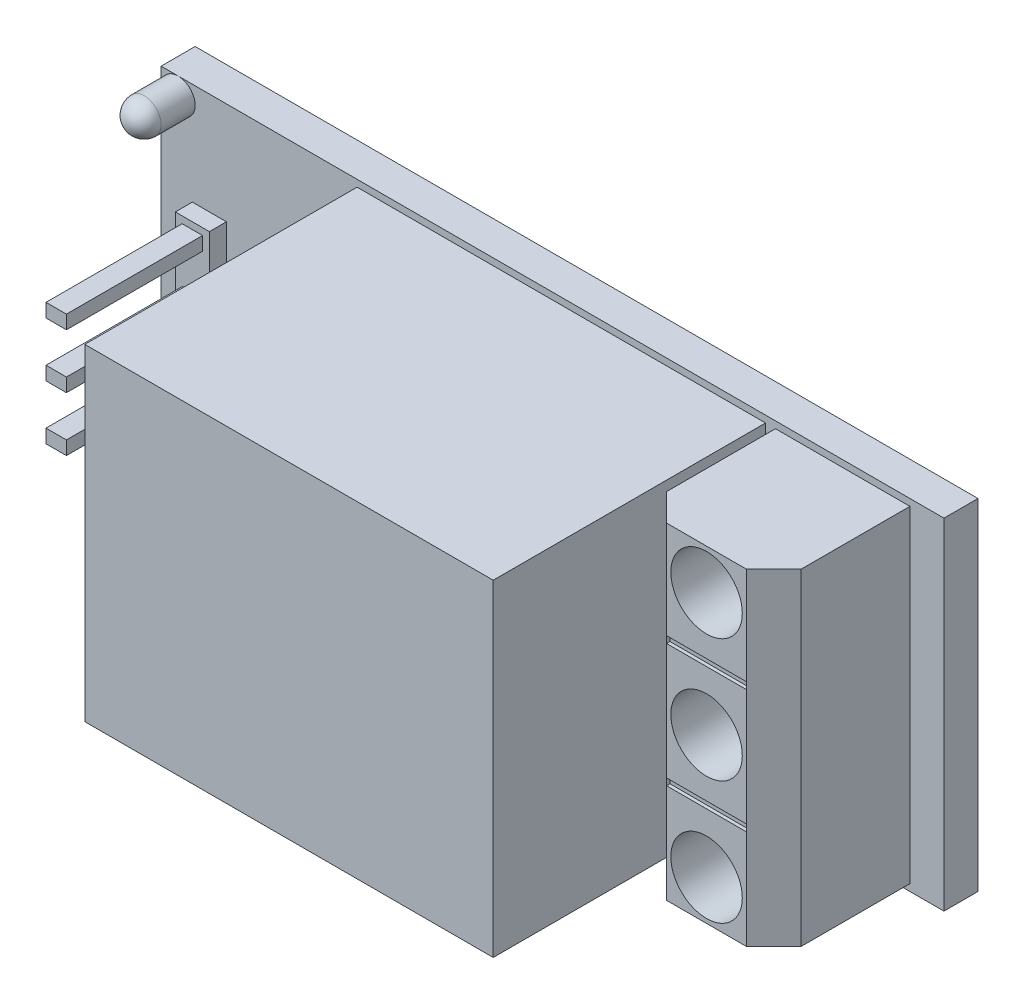
SolidWorks part; units mm, degrees
ref_plane "Front Plane" through (0, 0, 0) normal (0, 0, 1) x (1, 0, 0)
ref_plane "Top Plane" through (0, 0, 0) normal (0, 1, 0) x (1, 0, 0)
ref_plane "Right Plane" through (0, 0, 0) normal (1, 0, 0) x (0, 0, -1)
sketch "Sketch1" plane through (0, 0, 0) normal (0, 0, 1) x (1, 0, 0)
  line L1 (0, 0) -> (23, 0)
  line L2 (0, 0) -> (0, -10)
  line L3 (0, -10) -> (23, -10)
  line L4 (23, 0) -> (23, -10)
  dimension "D1" = 10
  dimension "D2" = 23
extrude "Boss-Extrude1" add sketch "Sketch1" along normal blind 1
sketch "Sketch2" plane through (0, 0, 1) normal (0, 0, 1) x (1, 0, 0)
  line L0 (23, 0) -> (0, 0) construction
  line L1 (22, -0.2) -> (18.05, -0.2)
  line L2 (22, -0.2) -> (22, -9.8)
  line L3 (22, -9.8) -> (18.05, -9.8)
  line L4 (18.05, -0.2) -> (18.05, -9.8)
  dimension "D1" = 1
  dimension "D2" = 0.2
  dimension "D3" = 0.2
  dimension "D4" = 3.95
extrude "Boss-Extrude2" add sketch "Sketch2" along normal blind 4
sketch "Sketch5" plane through (0, 0, 1) normal (0, 0, 1) x (1, 0, 0)
  line L1 (17.7578, -0.2) -> (5.7578, -0.2)
  line L2 (17.7578, -0.2) -> (17.7578, -9.8)
  line L3 (17.7578, -9.8) -> (5.7578, -9.8)
  line L4 (5.7578, -0.2) -> (5.7578, -9.8)
  point P4 (0, 0)
  point P5 (16.7151, -0.2)
  dimension "D1" = 12
extrude "Boss-Extrude3" add sketch "Sketch5" along normal blind 8
sketch "Sketch6" plane through (0, -9.8, 0) normal (0, -1, 0) x (1, 0, 0)
  line L0 (21.2, 5) -> (22, 4.2)
  line L1 (18.05, 5) -> (22, 5) construction
  line L2 (22, 5) -> (22, 1) construction
  line L3 (22, 4.2) -> (22, 5)
  line L4 (22, 5) -> (21.2, 5)
  line L5 (18.05, 5) -> (18.85, 5)
  line L6 (18.85, 5) -> (18.05, 4.2)
  line L7 (18.05, 5) -> (18.05, 1) construction
  line L8 (18.05, 4.2) -> (18.05, 5)
  dimension "D1" = 0.8
  dimension "D2" = 0.8
  dimension "D3" = 1.1314
  dimension "D4" = 0.8
  dimension "D5" = 0.8
  dimension "D6" = 1.1314
extrude "Cut-Extrude1" cut sketch "Sketch6" against normal up to next
sketch "Sketch7" plane through (0, 0, 5) normal (0, 0, 1) x (1, 0, 0)
  line L0 (18.85, -9.8) -> (21.2, -9.8) construction
  line L1 (20.025, -9.8) -> (20.025, -0.2) construction
  line L2 (21.2, -0.2) -> (18.85, -0.2) construction
  line L3 (18.85, -0.2) -> (18.85, -9.8) construction
  line L4 (18.85, -9.8) -> (21.2, -9.8)
  line L5 (18.85, -9.8) -> (18.85, -7.45)
  line L6 (18.85, -7.45) -> (21.2, -7.45)
  line L8 (21.2, -0.2) -> (21.2, -9.8) construction
  line L17 (21.2, -9.8) -> (21.2, -7.45)
  line L18 (21.2, -6.18) -> (21.2, -3.83)
  line L19 (18.85, -3.83) -> (21.2, -3.83)
  line L20 (18.85, -6.18) -> (18.85, -3.83)
  line L21 (18.85, -6.18) -> (21.2, -6.18)
  line L22 (21.2, -2.56) -> (21.2, -0.21)
  line L23 (18.85, -0.21) -> (21.2, -0.21)
  line L24 (18.85, -2.56) -> (18.85, -0.21)
  line L25 (18.85, -2.56) -> (21.2, -2.56)
  circle A0 centre (20.025, -8.625) radius 1.05
  circle A1 centre (20.025, -5.005) radius 1.05
  circle A2 centre (20.025, -1.385) radius 1.05
  point P2 (20.025, -9.8)
  point P10 (18.85, -8.625)
  point P16 (20.025, -8.625)
  dimension "D1" = 2.35
  dimension "D2" = 2.35
  dimension "D4" = 2.1
  dimension "D3" = 3
  dimension "D5" = 3
extrude "Cut-Extrude3" cut sketch "Sketch7" against normal blind 1.5 contours A0 | A1 | A2
sketch "Sketch9" plane through (0, 0, 5) normal (0, 0, 1) x (1, 0, 0)
  line L0 (18.85, -9.8) -> (21.2, -9.8)
  line L1 (18.85, -0.2) -> (18.85, -9.8) construction
  line L2 (18.85, -6.8837) -> (21.2, -6.8837)
  line L3 (18.85, -6.8837) -> (18.85, -6.6837)
  line L4 (18.85, -6.6837) -> (21.2, -6.6837)
  line L5 (21.2, -6.8837) -> (21.2, -6.6837)
  line L6 (21.2, -0.2) -> (21.2, -9.8) construction
  line L8 (18.85, -3.264) -> (21.2, -3.264)
  line L9 (18.85, -3.264) -> (18.85, -3.064)
  line L10 (18.85, -3.064) -> (21.2, -3.064)
  line L11 (21.2, -3.264) -> (21.2, -3.064)
  line M13 (21.2, -9.8) -> (21.2, -0.2)
  line M15 (18.85, -0.2) -> (18.85, -9.8)
  dimension "D1" = 9.6
  dimension "D2" = 0.2
  dimension "D3" = 0.2
extrude "Cut-Extrude4" cut sketch "Sketch9" against normal blind 0.1 contours L4 L2 M15 M13 | L9 L8 L11 L10
sketch "Sketch10" plane through (0, 0, 1) normal (0, 0, 1) x (1, 0, 0)
  line L0 (1.5794, -4.9531) -> (1.5794, -5.1637)
  line L1 (1.9183, -7) -> (0.9183, -7)
  line L2 (1.9183, -7) -> (1.9183, -3)
  line L3 (1.9183, -3) -> (0.9183, -3)
  line L4 (0.9183, -7) -> (0.9183, -3)
  line L5 (23, 0) -> (0, 0) construction
  line L6 (1.5794, -4.9531) -> (1.2044, -4.9531)
  line L7 (1.5794, -3.2531) -> (1.2044, -3.2531)
  line L8 (1.5794, -3.2531) -> (1.5794, -3.4637)
  line L9 (1.5794, -3.4637) -> (1.2044, -3.4637)
  line L10 (1.2044, -3.2531) -> (1.2044, -3.4637)
  line L11 (1.2044, -4.9531) -> (1.2044, -5.1637)
  line L12 (1.5794, -5.1637) -> (1.2044, -5.1637)
  line L13 (1.5794, -6.6531) -> (1.5794, -6.8637)
  line L14 (1.5794, -6.6531) -> (1.2044, -6.6531)
  line L15 (1.2044, -6.6531) -> (1.2044, -6.8637)
  line L16 (1.5794, -6.8637) -> (1.2044, -6.8637)
  dimension "D1" = 1
  dimension "D2" = 3
  dimension "D3" = 4
  dimension "D4" = 3
  dimension "D5" = 3
extrude "Boss-Extrude4" add sketch "Sketch10" along normal blind 0.5 contours L2 L1 L4 L3
sketch "Sketch11" plane through (0, 0, 1.5) normal (0, 0, 1) x (1, 0, 0)
  line L0 (1.7183, -4.8) -> (1.7183, -5.2)
  line L1 (1.7183, -3.2) -> (1.1183, -3.2)
  line L2 (1.7183, -3.2) -> (1.7183, -3.6)
  line L3 (1.7183, -3.6) -> (1.1183, -3.6)
  line L4 (1.1183, -3.2) -> (1.1183, -3.6)
  line L13 (1.7183, -4.8) -> (1.1183, -4.8)
  line L14 (1.1183, -4.8) -> (1.1183, -5.2)
  line L15 (1.7183, -5.2) -> (1.1183, -5.2)
  line L16 (1.7183, -6.4) -> (1.7183, -6.8)
  line L17 (1.7183, -6.4) -> (1.1183, -6.4)
  line L18 (1.1183, -6.4) -> (1.1183, -6.8)
  line L19 (1.7183, -6.8) -> (1.1183, -6.8)
  dimension "D1" = 0.4
  dimension "D2" = 0.2
  dimension "D3" = 0.6
  dimension "D4" = 0.2
  dimension "D5" = 3
extrude "Boss-Extrude5" add sketch "Sketch11" along normal blind 4
sketch "Sketch12" plane through (0, 0, 1) normal (0, 0, 1) x (1, 0, 0)
  line L0 (0, 0) -> (1, 0) construction
  line L1 (23, 0) -> (0, 0) construction
  line L2 (1, 0) -> (1, -1) construction
  line L3 (1, -1) -> (0, -1) construction
  line L4 (0, 0) -> (0, -10) construction
  line L5 (0, -1) -> (0, 0) construction
  line L6 (0.5, 0) -> (0.5, -1) construction
  line L7 (1, -0.5) -> (0, -0.5) construction
  line L8 (0, -10) -> (0, -9) construction
  line L9 (0, -9) -> (1, -9) construction
  line L10 (1, -9) -> (1, -10) construction
  line L11 (0, -10) -> (23, -10) construction
  line L12 (1, -10) -> (0, -10) construction
  line L13 (1, -9.5) -> (0, -9.5) construction
  circle A1 centre (0.5, -9.5) radius 0.5
  circle A2 centre (0.5, -0.5) radius 0.5
  dimension "D1" = 1
  dimension "D2" = 1
  dimension "D3" = 1
  dimension "D4" = 1
extrude "Boss-Extrude6" add sketch "Sketch12" along normal blind 1.5
fillet "Fillet3" radius 0.5 2 edges at (1, -9.5, 2.5) (1, -0.5, 2.5)
